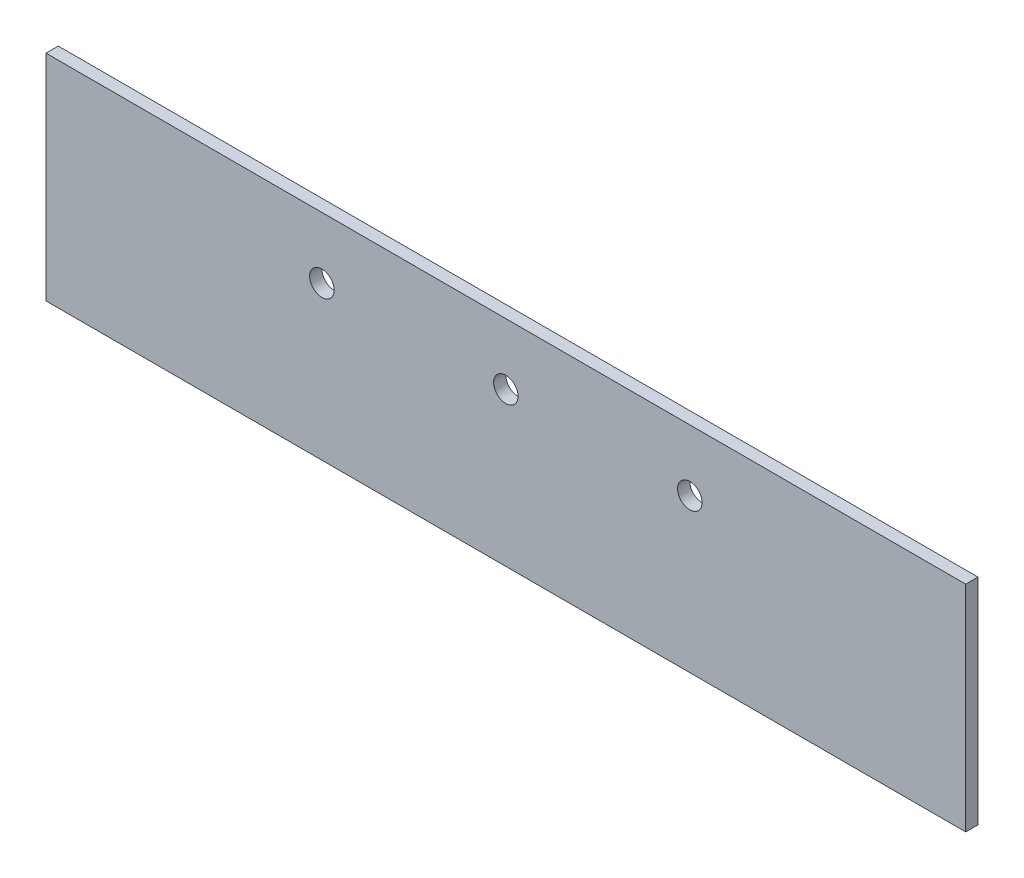
SolidWorks part; units mm, degrees
ref_plane "Front Plane" through (0, 0, 0) normal (0, 0, 1) x (1, 0, 0)
ref_plane "Top Plane" through (0, 0, 0) normal (0, 1, 0) x (1, 0, 0)
ref_plane "Right Plane" through (0, 0, 0) normal (1, 0, 0) x (0, 0, -1)
sketch "Sketch1" plane through (0, 0, 0) normal (0, 0, 1) x (1, 0, 0)
  line L1 (-75, -17.5) -> (75, -17.5)
  line L2 (-75, -17.5) -> (-75, 17.5)
  line L3 (-75, 17.5) -> (75, 17.5)
  line L4 (75, -17.5) -> (75, 17.5)
  line L5 (0, 17.5) -> (0, -17.5) construction
  line L6 (-75, 0) -> (75, 0) construction
  point P0 (0, 0)
  dimension "D1" = 150
  dimension "D2" = 35
extrude "Boss-Extrude1" add sketch "Sketch1" along normal blind 2
sketch "Sketch2" plane through (0, 0, 0) normal (0, 0, -1) x (-1, 0, 0)
  line L0 (0, 0) -> (0, 17.5) construction
  line L1 (-75, 17.5) -> (75, 17.5) construction
  line L3 (80, 7.5) -> (-30, 7.5) construction
  circle A1 centre (30, 7.5) radius 2
  circle A2 centre (0, 7.5) radius 2
  circle A3 centre (-30, 7.5) radius 2
  point P13 (0, 0)
  dimension "D1" = 4
  dimension "D3" = 10
  dimension "D7" = 30
  dimension "D8" = 30
extrude "fix hole" cut sketch "Sketch2" against normal through all
